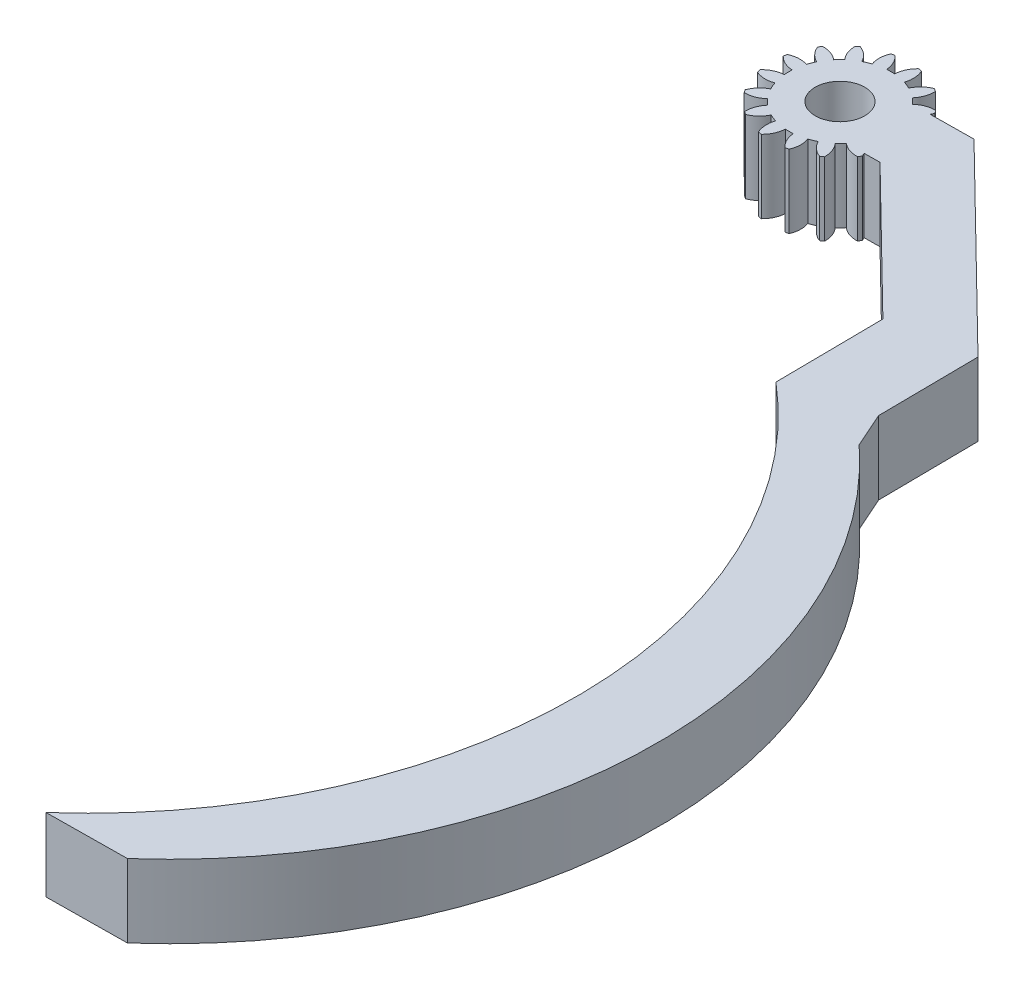
SolidWorks part; units mm, degrees
ref_plane "Front Plane" through (0, 0, 0) normal (0, 0, 1) x (1, 0, 0)
ref_plane "Top Plane" through (0, 0, 0) normal (0, 1, 0) x (1, 0, 0)
ref_plane "Right Plane" through (0, 0, 0) normal (1, 0, 0) x (0, 0, -1)
sketch "Sketch1" plane through (0, 0, 0) normal (0, 1, 0) x (1, 0, 0)
  line L0 (-58.7445, 21.1888) -> (-58.8636, 32.4482)
  line L1 (-58.8636, 32.4482) -> (-73.1523, 46.4378)
  line L2 (-73.1523, 46.4378) -> (-74.7978, 46.4204)
  line L3 (-74.8713, 53.3753) -> (-70.3461, 53.4231)
  line L4 (-70.3461, 53.4231) -> (-50.484, 33.9768)
  line L5 (-50.484, 33.9768) -> (-50.3734, 23.52)
  line L6 (-50.3734, 23.52) -> (-48.7578, 19.8722)
  line L7 (-49.5368, -55.5736) -> (-57.9315, -55.6624)
  arc A0 (-57.9315, -55.6624) -> (-58.7445, 21.1888) centre (-91.5619, -17.5883) ccw
  arc A1 (-74.639, 46.0866) -> (-74.7978, 46.4204) centre (-77.006, 45.1652) ccw
  arc A2 (-74.8421, 45.7756) -> (-74.639, 46.0866) centre (-80.72, 49.8356) ccw
  arc A3 (-76.6222, 46.4011) -> (-74.8421, 45.7756) centre (-74.9504, 48.3133) ccw
  arc A4 (-77.1995, 45.8114) -> (-76.6222, 46.4011) centre (-80.72, 49.8356) ccw
  arc A5 (-76.5365, 44.0449) -> (-77.1995, 45.8114) centre (-79.0759, 44.0994) ccw
  arc A6 (-76.8432, 43.8352) -> (-76.5365, 44.0449) centre (-80.72, 49.8356) ccw
  arc A7 (-78.2485, 45.0944) -> (-76.8432, 43.8352) centre (-75.9721, 46.2212) ccw
  arc A8 (-79.0075, 44.7705) -> (-78.2485, 45.0944) centre (-80.72, 49.8356) ccw
  arc A9 (-79.071, 42.8847) -> (-79.0075, 44.7705) centre (-81.3962, 43.907) ccw
  arc A10 (-79.4345, 42.8084) -> (-79.071, 42.8847) centre (-80.72, 49.8356) ccw
  arc A11 (-80.251, 44.5095) -> (-79.4345, 42.8084) centre (-77.7167, 44.6794) ccw
  arc A12 (-81.0762, 44.5007) -> (-80.251, 44.5095) centre (-80.72, 49.8356) ccw
  arc A13 (-81.8565, 42.7828) -> (-81.0762, 44.5007) centre (-83.6135, 44.617) ccw
  arc A14 (-82.2215, 42.8514) -> (-81.8565, 42.7828) centre (-80.72, 49.8356) ccw
  arc A15 (-82.3249, 44.7354) -> (-82.2215, 42.8514) centre (-79.9184, 43.9226) ccw
  arc A16 (-83.0906, 45.0431) -> (-82.3249, 44.7354) centre (-80.72, 49.8356) ccw
  arc A17 (-84.4689, 43.7546) -> (-83.0906, 45.0431) centre (-85.3903, 46.1216) ccw
  arc A18 (-84.7799, 43.9577) -> (-84.4689, 43.7546) centre (-80.72, 49.8356) ccw
  arc A19 (-84.1544, 45.7378) -> (-84.7799, 43.9577) centre (-82.2423, 44.066) ccw
  arc A20 (-84.7441, 46.3151) -> (-84.1544, 45.7378) centre (-80.72, 49.8356) ccw
  arc A21 (-86.5106, 45.6521) -> (-84.7441, 46.3151) centre (-86.4561, 48.1915) ccw
  arc A22 (-86.7203, 45.9588) -> (-86.5106, 45.6521) centre (-80.72, 49.8356) ccw
  arc A23 (-85.4611, 47.3641) -> (-86.7203, 45.9588) centre (-84.3343, 45.0877) ccw
  arc A24 (-85.785, 48.1231) -> (-85.4611, 47.3641) centre (-80.72, 49.8356) ccw
  arc A25 (-87.6708, 48.1866) -> (-85.785, 48.1231) centre (-86.6486, 50.5118) ccw
  arc A26 (-87.7471, 48.5501) -> (-87.6708, 48.1866) centre (-80.72, 49.8356) ccw
  arc A27 (-86.046, 49.3666) -> (-87.7471, 48.5501) centre (-85.8761, 46.8323) ccw
  arc A28 (-86.0548, 50.1918) -> (-86.046, 49.3666) centre (-80.72, 49.8356) ccw
  arc A29 (-87.7727, 50.9721) -> (-86.0548, 50.1918) centre (-85.9385, 52.7291) ccw
  arc A30 (-87.7041, 51.3371) -> (-87.7727, 50.9721) centre (-80.72, 49.8356) ccw
  arc A31 (-85.8201, 51.4405) -> (-87.7041, 51.3371) centre (-86.6329, 49.034) ccw
  arc A32 (-85.5124, 52.2062) -> (-85.8201, 51.4405) centre (-80.72, 49.8356) ccw
  arc A33 (-86.8009, 53.5845) -> (-85.5124, 52.2062) centre (-84.4339, 54.5059) ccw
  arc A34 (-86.5979, 53.8955) -> (-86.8009, 53.5845) centre (-80.72, 49.8356) ccw
  arc A35 (-84.8177, 53.27) -> (-86.5979, 53.8955) centre (-86.4896, 51.3579) ccw
  arc A36 (-84.2404, 53.8597) -> (-84.8177, 53.27) centre (-80.72, 49.8356) ccw
  arc A37 (-84.9034, 55.6263) -> (-84.2404, 53.8597) centre (-82.364, 55.5717) ccw
  arc A38 (-84.5967, 55.8359) -> (-84.9034, 55.6263) centre (-80.72, 49.8356) ccw
  arc A39 (-83.1914, 54.5767) -> (-84.5967, 55.8359) centre (-85.4678, 53.4499) ccw
  arc A40 (-82.4324, 54.9006) -> (-83.1914, 54.5767) centre (-80.72, 49.8356) ccw
  arc A41 (-82.3689, 56.7864) -> (-82.4324, 54.9006) centre (-80.0437, 55.7642) ccw
  arc A42 (-82.0054, 56.8627) -> (-82.3689, 56.7864) centre (-80.72, 49.8356) ccw
  arc A43 (-81.1889, 55.1616) -> (-82.0054, 56.8627) centre (-83.7232, 54.9917) ccw
  arc A44 (-80.3637, 55.1704) -> (-81.1889, 55.1616) centre (-80.72, 49.8356) ccw
  arc A45 (-79.5834, 56.8883) -> (-80.3637, 55.1704) centre (-77.8264, 55.0541) ccw
  arc A46 (-79.2184, 56.8197) -> (-79.5834, 56.8883) centre (-80.72, 49.8356) ccw
  arc A47 (-79.115, 54.9357) -> (-79.2184, 56.8197) centre (-81.5215, 55.7485) ccw
  arc A48 (-78.3493, 54.628) -> (-79.115, 54.9357) centre (-80.72, 49.8356) ccw
  arc A49 (-76.971, 55.9165) -> (-78.3493, 54.628) centre (-76.0496, 53.5495) ccw
  arc A50 (-76.66, 55.7135) -> (-76.971, 55.9165) centre (-80.72, 49.8356) ccw
  arc A51 (-77.2855, 53.9333) -> (-76.66, 55.7135) centre (-79.1977, 55.6052) ccw
  arc A52 (-76.6958, 53.356) -> (-77.2855, 53.9333) centre (-80.72, 49.8356) ccw
  arc A53 (-74.9293, 54.019) -> (-76.6958, 53.356) centre (-74.9838, 51.4796) ccw
  arc A54 (-74.7196, 53.7123) -> (-74.9293, 54.019) centre (-80.72, 49.8356) ccw
  arc A55 (-74.8713, 53.3753) -> (-74.7196, 53.7123) centre (-77.1056, 54.5834) ccw
  arc A56 (-49.5368, -55.5736) -> (-48.7578, 19.8722) centre (-83.1671, -17.4995) ccw
  circle A57 centre (-80.72, 49.8356) radius 2.585
extrude "Boss-Extrude1" add sketch "Sketch1" along normal blind 7.62
